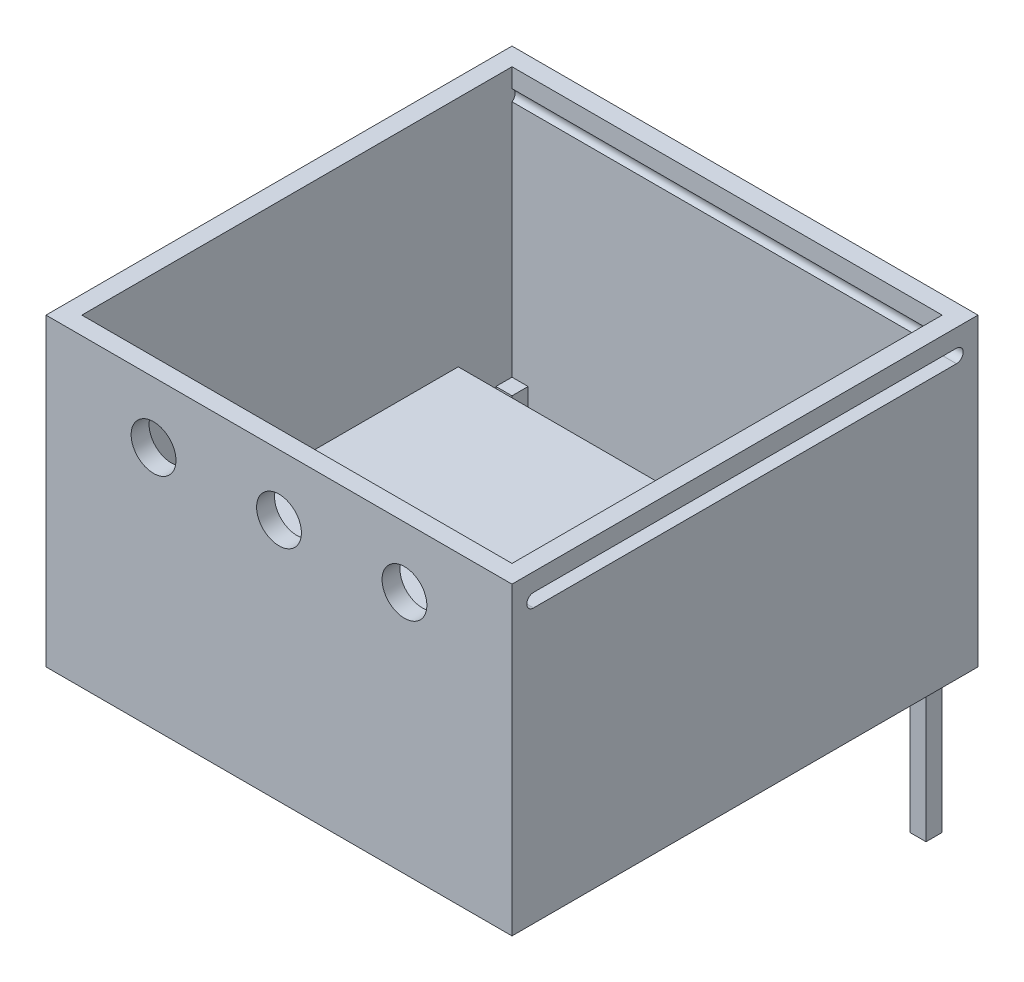
SolidWorks part; units mm, degrees
ref_plane "Ebene vorne" through (0, 0, 0) normal (0, 0, 1) x (1, 0, 0)
ref_plane "Ebene oben" through (0, 0, 0) normal (0, 1, 0) x (1, 0, 0)
ref_plane "Ebene rechts" through (0, 0, 0) normal (1, 0, 0) x (0, 0, -1)
sketch "Skizze1" plane through (0, 0, 0) normal (0, 1, 0) x (1, 0, 0)
  line L1 (25, -25) -> (-25, -25)
  line L2 (25, -25) -> (25, 25)
  line L3 (25, 25) -> (-25, 25)
  line L4 (-25, -25) -> (-25, 25)
  line L5 (25, -25) -> (-25, 25) construction
  line L6 (25, 25) -> (-25, -25) construction
  point P0 (0, 0)
  dimension "D1" = 50
  dimension "D2" = 50
extrude "Aufsatz-Linear austragen1" add sketch "Skizze1" along normal blind 8
sketch "Skizze2" plane through (0, 8, 0) normal (0, 1, 0) x (1, 0, 0)
  line L0 (-25, -25) -> (25, -25) construction
  line L1 (25, -25) -> (25, 25) construction
  line L2 (25, 25) -> (-25, 25) construction
  line L3 (-25, 25) -> (-25, -25) construction
  line L4 (-25, -25) -> (25, -25)
  line L5 (25, -25) -> (25, 25)
  line L6 (25, 25) -> (-25, 25)
  line L7 (-25, 25) -> (-25, -25)
extrude "Linear-Austragen-Dünn1" add sketch "Skizze2" along normal blind 26 and the other way up to surface thin other way up to face at (0, 0, 0) thin type mid plane wall 2
sketch "Skizze3" plane through (26, 0, 0) normal (1, 0, 0) x (0, 0, -1)
  line L0 (-23.6, 31.25) -> (23.6, 31.25) construction
  line L1 (-23.6, 32) -> (23.6, 32)
  line L2 (-23.6, 30.5) -> (23.6, 30.5)
  line L3 (-26, 34) -> (26, 34) construction
  line L6 (-26, 0) -> (-26, 34) construction
  line L7 (26, 0) -> (26, 34) construction
  arc A0 (-23.6, 32) -> (-23.6, 30.5) centre (-23.6, 31.25) ccw
  arc A1 (23.6, 30.5) -> (23.6, 32) centre (23.6, 31.25) ccw
  point P2 (0, 31.25)
  dimension "D1" = 1.5
  dimension "D2" = 2
  dimension "D3" = 2.4
  dimension "D4" = 2.4
  dimension "D5" = 47.2
extrude "Schnitt-Linear austragen1" cut sketch "Skizze3" against normal up to surface (50 mm away) up to face at (-24, 21, 0)
sketch "Skizze4" plane through (0, 8, 0) normal (0, 1, 0) x (1, 0, 0)
  line L0 (24, -24) -> (24, 24) construction
  line L1 (-24, 24) -> (24, 24)
  line L2 (-24, 24) -> (-24, 18)
  line L3 (-24, 18) -> (24, 18)
  line L4 (24, 24) -> (24, 18)
  dimension "D1" = 6
extrude "Schnitt-Linear austragen2" cut sketch "Skizze4" against normal up to next
sketch "Skizze5" plane through (0, 0, 26) normal (0, 0, 1) x (1, 0, 0)
  line L0 (-26, 34) -> (26, 34) construction
  circle A0 centre (-14, 27.2) radius 2.5
  circle A1 centre (0, 27.2) radius 2.5
  circle A2 centre (14, 27.2) radius 2.5
  dimension "D1" = 5
  dimension "D2" = 28
  dimension "D3" = 14
  dimension "D4" = 6.8
extrude "Schnitt-Linear austragen3" cut sketch "Skizze5" against normal up to next
sketch "Skizze6" plane through (0, 0, 0) normal (0, -1, 0) x (1, 0, 0)
  line L1 (-24, -24) -> (-22.2, -24)
  line L2 (-24, -24) -> (-24, -22.2)
  line L3 (-24, -22.2) -> (-22.2, -22.2)
  line L4 (-22.2, -24) -> (-22.2, -22.2)
  line L5 (24, -24) -> (22.2, -24)
  line L6 (24, -24) -> (24, -22.2)
  line L7 (24, -22.2) -> (22.2, -22.2)
  line L8 (22.2, -24) -> (22.2, -22.2)
  dimension "D1" = 1.8
extrude "Aufsatz-Linear austragen2" add sketch "Skizze6" along normal blind 16 and the other way blind 4 separate body
